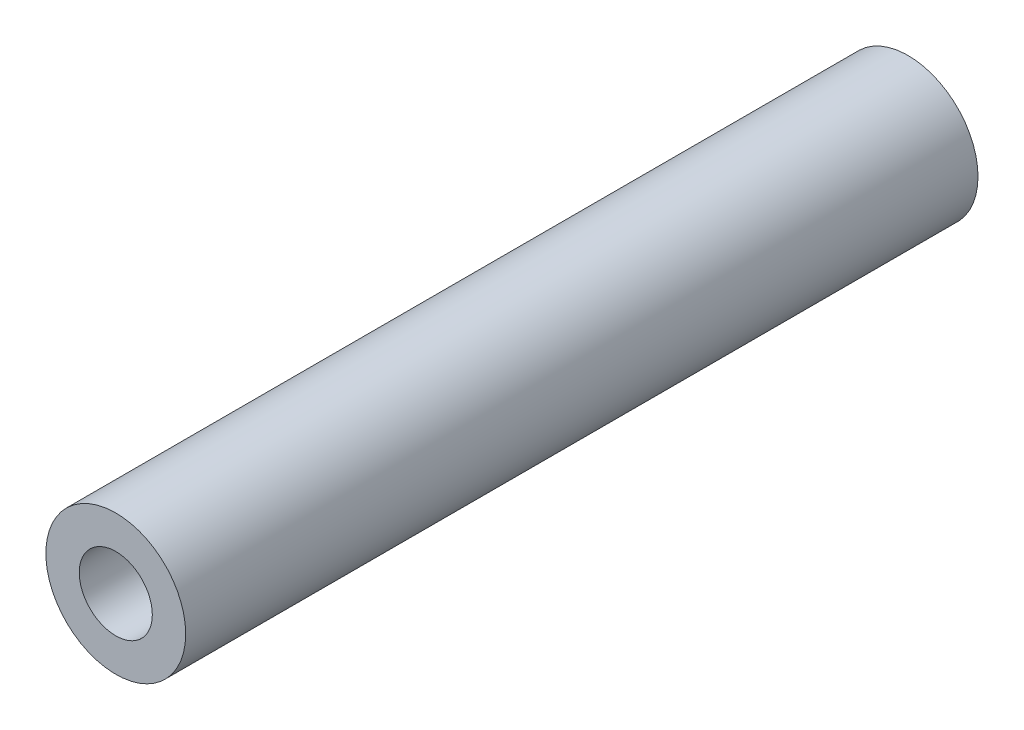
SolidWorks part; units mm, degrees
material "6061-T6 (SS)"
ref_plane "Front Plane" through (0, 0, 0) normal (0, 0, 1) x (1, 0, 0)
ref_plane "Top Plane" through (0, 0, 0) normal (0, 1, 0) x (1, 0, 0)
ref_plane "Right Plane" through (0, 0, 0) normal (1, 0, 0) x (0, 0, -1)
sketch "Sketch1" plane through (0, 0, 0) normal (0, 0, 1) x (1, 0, 0)
  circle A0 centre (0, 0) radius 2.4892
  circle A1 centre (0, 0) radius 4.7625
  dimension "D1" = 4.9784
  dimension "D2" = 9.525
extrude "Boss-Extrude1" add sketch "Sketch1" along normal blind 53.975
